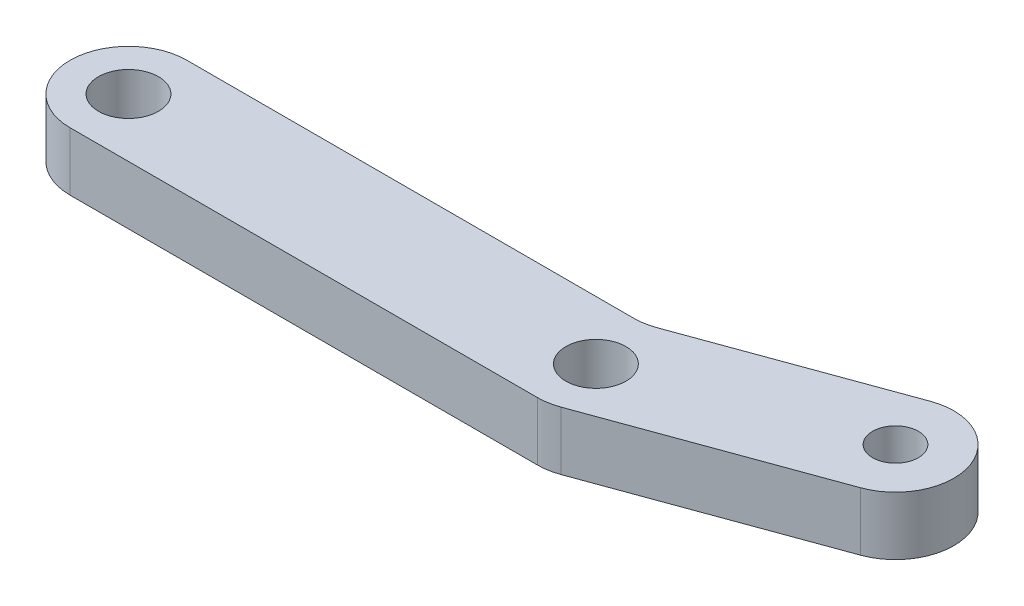
SolidWorks part; units mm, degrees
material "6061-T6 (SS)"
ref_plane "Front Plane" through (0, 0, 0) normal (0, 0, 1) x (1, 0, 0)
ref_plane "Top Plane" through (0, 0, 0) normal (0, 1, 0) x (1, 0, 0)
ref_plane "Right Plane" through (0, 0, 0) normal (1, 0, 0) x (0, 0, -1)
sketch "Sketch1" plane through (0, 0, 0) normal (0, 1, 0) x (1, 0, 0)
  line L0 (0, 0) -> (50.8, 0) construction
  line L1 (0, 6.35) -> (50.8, 6.35)
  line L2 (0, -6.35) -> (50.8, -6.35)
  arc A0 (0, 6.35) -> (0, -6.35) centre (0, 0) ccw
  arc A1 (50.8, -6.35) -> (50.8, 6.35) centre (50.8, 0) ccw
  circle A2 centre (0, 0) radius 3.2639
  circle A3 centre (50.8, 0) radius 3.2639
  point P3 (25.4, 0)
  dimension "D1" = 6.35
  dimension "D3" = 6.5278
  dimension "D2" = 50.8
extrude "Boss-Extrude1" add sketch "Sketch1" along normal mid plane 6.35
sketch "Sketch3" plane through (0, -3.175, 0) normal (0, -1, 0) x (1, 0, 0)
  line L0 (52.9718, 5.967) -> (76.84, -2.7203)
  line L1 (48.6282, -5.967) -> (72.4964, -14.6544)
  line L4 (0, -6.35) -> (50.8, -6.35)
  line L5 (50.8, 6.35) -> (0, 6.35)
  line L6 (0, -6.35) -> (50.8, -6.35)
  line L7 (50.8, 6.35) -> (0, 6.35)
  arc A0 (50.8, -6.35) -> (50.8, 6.35) centre (50.8, 0) ccw construction
  arc A1 (72.4964, -14.6544) -> (76.84, -2.7203) centre (74.6682, -8.6873) ccw
  circle A2 centre (74.6682, -8.6873) radius 2.4892
  arc A3 (0, 6.35) -> (0, -6.35) centre (0, 0) ccw
  arc A4 (50.8, -6.35) -> (50.8, 6.35) centre (50.8, 0) ccw
  arc A5 (0, 6.35) -> (0, -6.35) centre (0, 0) ccw
  arc A6 (50.8, -6.35) -> (50.8, 6.35) centre (50.8, 0) ccw
  point P9 (66.8669, -20.6722)
  arc M10 (50.8, -6.35) -> (50.8, 6.35) centre (50.8, 0) ccw
  line M11 (50.8, 6.35) -> (0, 6.35)
  dimension "D2" = 4.9784
  dimension "D3" = 160
  dimension "D4" = 25.4
  dimension "D1" = 0
extrude "Boss-Extrude2" add sketch "Sketch3" against normal up to surface (6.35 mm away) contours L1 A1 L0 A2 M11 M10
fillet "Fillet2" radius 6.35 1 edges at (49.6803, 0, -6.35)
